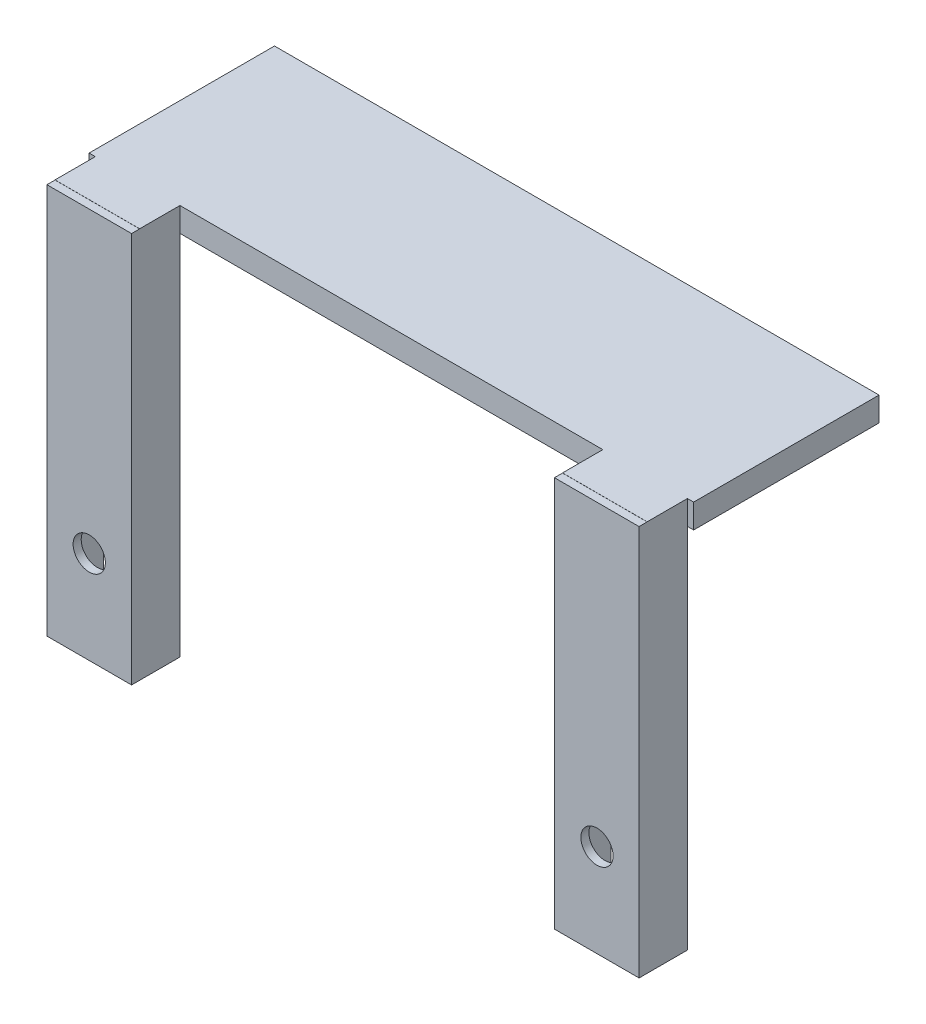
SolidWorks part; units mm, degrees
ref_plane "Front Plane" through (0, 0, 0) normal (0, 0, 1) x (1, 0, 0)
ref_plane "Top Plane" through (0, 0, 0) normal (0, 1, 0) x (1, 0, 0)
ref_plane "Right Plane" through (0, 0, 0) normal (1, 0, 0) x (0, 0, -1)
sketch "Sketch1" plane through (0, 0, 0) normal (0, 1, 0) x (1, 0, 0)
  line L1 (-37.5, -11.5) -> (37.5, -11.5)
  line L2 (-37.5, -11.5) -> (-37.5, 11.5)
  line L3 (-37.5, 11.5) -> (37.5, 11.5)
  line L4 (37.5, -11.5) -> (37.5, 11.5)
  line L5 (-37.5, -11.5) -> (37.5, 11.5) construction
  line L6 (-37.5, 11.5) -> (37.5, -11.5) construction
  point P0 (0, 0)
extrude "Boss-Extrude1" add sketch "Sketch1" along normal blind 3
sketch "Sketch2" plane through (0, 0, 11.5) normal (0, 0, 1) x (1, 0, 0)
  line L3 (27.2303, 0) -> (27.2303, -45.5149)
  line L5 (-35.4803, -45.5149) -> (-37.4966, -45.5149) construction
  line L7 (-12.4738, -45.5149) -> (-27.4803, -45.5149) construction
  line L14 (-35.7303, -45.5149) -> (-36.7303, -45.5149)
  line L15 (-27.2303, -45.5149) -> (-26.2303, -45.5149)
  line L16 (-26.2303, -45.5149) -> (-26.2303, 3)
  line L17 (-37.5, 3) -> (37.5, 3) construction
  line L19 (-26.2303, 3) -> (-36.7303, 3)
  line L20 (-36.7303, 3) -> (-36.7303, -45.5149)
  line L22 (-35.7303, -45.5149) -> (-35.7303, 0)
  line L23 (-37.5, 0) -> (37.5, 0) construction
  line L24 (-35.7303, 0) -> (-27.2303, 0)
  line L25 (-27.2303, 0) -> (-27.2303, -45.5149)
  line L26 (35.7303, 0) -> (27.2303, 0)
  line L27 (35.7303, -45.5149) -> (35.7303, 0)
  line L28 (36.7303, 3) -> (36.7303, -45.5149)
  line L29 (26.2303, 3) -> (36.7303, 3)
  line L30 (26.2303, -45.5149) -> (26.2303, 3)
  line L31 (27.2303, -45.5149) -> (26.2303, -45.5149)
  line L32 (35.7303, -45.5149) -> (36.7303, -45.5149)
extrude "Boss-Extrude4" add sketch "Sketch2" along normal blind 5
sketch "Sketch3" plane through (0, -45.5149, 0) normal (0, -1, 0) x (1, 0, 0)
  line L0 (-36.7303, 16.5) -> (-26.2303, 16.5)
  line L1 (-26.2303, 16.5) -> (-26.2303, 17.5)
  line L2 (-26.2303, 17.5) -> (-36.7303, 17.5)
  line L3 (-36.7303, 17.5) -> (-36.7303, 16.5)
  line L4 (26.2303, 16.5) -> (36.7303, 16.5)
  line L5 (36.7303, 16.5) -> (36.7303, 17.5)
  line L6 (36.7303, 17.5) -> (26.2303, 17.5)
  line L7 (26.2303, 17.5) -> (26.2303, 16.5)
extrude "Boss-Extrude5" add sketch "Sketch3" against normal blind 48.5
sketch "Sketch4" plane through (0, 0, 16.5) normal (0, 0, -1) x (-1, 0, 0)
  circle A0 centre (31.4813, -34.0121) radius 2
  circle A1 centre (-31.5034, -34.0149) radius 2
extrude "Cut-Extrude1" cut sketch "Sketch4" against normal through all
